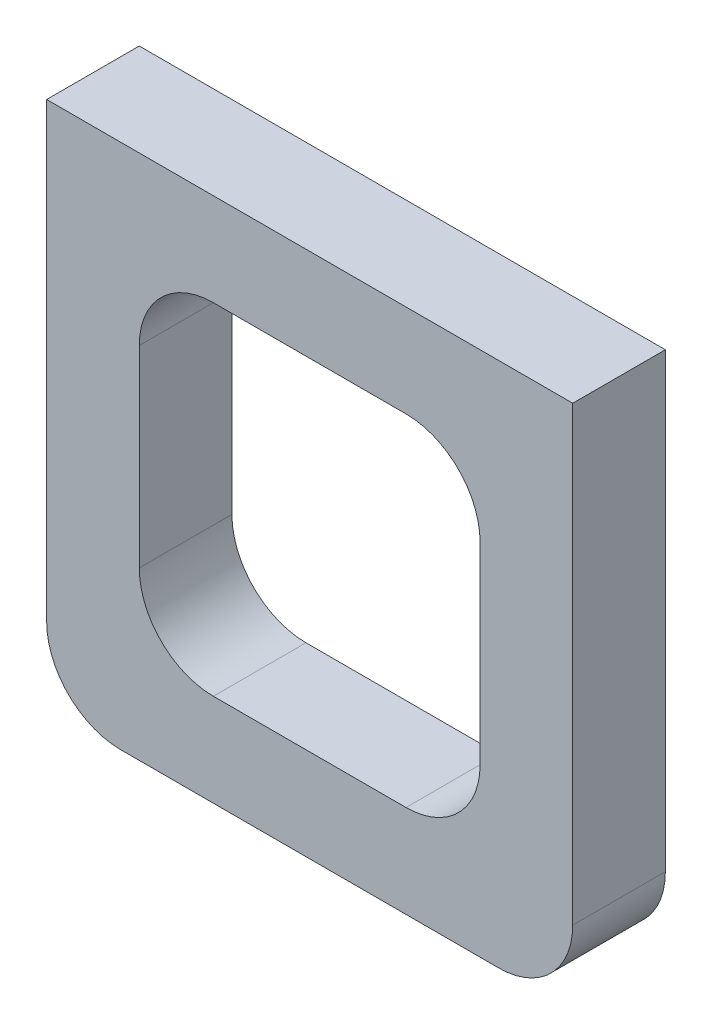
SolidWorks part; units mm, degrees
material "Pine"
ref_plane "Front Plane" through (0, 0, 0) normal (0, 0, 1) x (1, 0, 0)
ref_plane "Top Plane" through (0, 0, 0) normal (0, 1, 0) x (1, 0, 0)
ref_plane "Right Plane" through (0, 0, 0) normal (1, 0, 0) x (0, 0, -1)
sketch "Sketch1" plane through (0, 0, 0) normal (0, 0, 1) x (1, 0, 0)
  line L0 (0, 5.08) -> (0, 36.068)
  line L6 (36.068, 36.068) -> (36.068, 5.08)
  line L7 (30.988, 0) -> (5.08, 0)
  line L8 (11.43, 6.35) -> (24.638, 6.35)
  line L9 (6.35, 11.43) -> (6.35, 24.638)
  line L10 (11.43, 29.718) -> (24.638, 29.718)
  line L11 (29.718, 11.43) -> (29.718, 24.638)
  line L12 (36.068, 36.068) -> (0, 36.068)
  arc A0 (11.43, 6.35) -> (6.35, 11.43) centre (11.43, 11.43) cw
  arc A1 (24.638, 6.35) -> (29.718, 11.43) centre (24.638, 11.43) ccw
  arc A2 (24.638, 29.718) -> (29.718, 24.638) centre (24.638, 24.638) cw
  arc A3 (6.35, 24.638) -> (11.43, 29.718) centre (11.43, 24.638) cw
  arc A4 (36.068, 5.08) -> (30.988, 0) centre (30.988, 5.08) cw
  arc A5 (0, 5.08) -> (5.08, 0) centre (5.08, 5.08) ccw
  point P5 (6.35, 6.35)
  point P13 (18.034, 0)
  point P17 (29.718, 29.718)
  point P20 (6.35, 29.718)
  point P25 (0, 0)
  dimension "D7" = 5.08
  dimension "D8" = 5.08
  dimension "D2" = 23.368
  dimension "D3" = 23.368
  dimension "D4" = 6.35
  dimension "D5" = 6.35
  dimension "D6" = 6.35
  dimension "D1" = 6.35
extrude "Boss-Extrude1" add sketch "Sketch1" along normal blind 6.35
equation "\"D1@Sketch1\"=\"D5@Sketch1\""
equation "\"D6@Sketch1\"=\"D5@Sketch1\""
equation "\"D4@Sketch1\"=\"D5@Sketch1\""
equation "\"D2@Sketch1\"=\"D3@Sketch1\""
